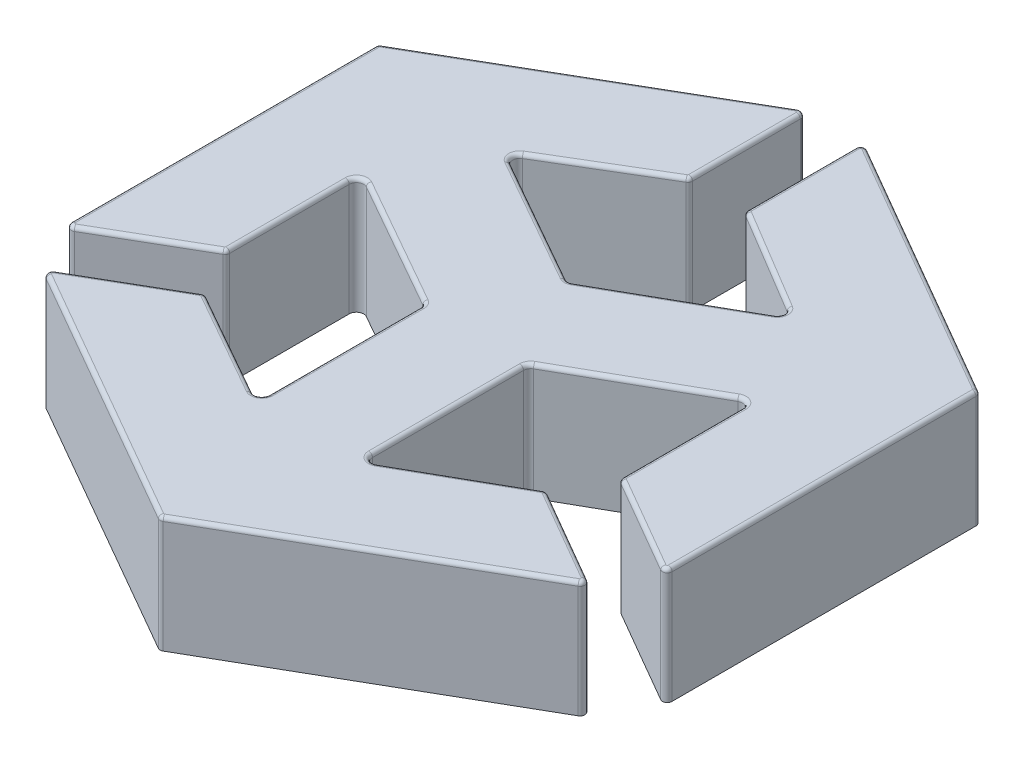
SolidWorks part; units mm, degrees
ref_plane "Front Plane" through (0, 0, 0) normal (0, 0, 1) x (1, 0, 0)
ref_plane "Top Plane" through (0, 0, 0) normal (0, 1, 0) x (1, 0, 0)
ref_plane "Right Plane" through (0, 0, 0) normal (1, 0, 0) x (0, 0, -1)
sketch "Sketch1" plane through (0, 0, 0) normal (0, 1, 0) x (1, 0, 0)
  line L0 (106.3333, 360) -> (531.6667, 360) construction
sketch "Sketch2" plane through (0, 0, 0) normal (0, 1, 0) x (1, 0, 0)
  line L1 (30.6854, 42.3674) -> (17.3949, 49.9061)
  line L2 (17.3796, 51.2019) -> (27.9558, 57.5366)
  line L3 (28.1989, 57.9656) -> (28.1989, 69.1104)
  line L4 (27.4483, 69.5431) -> (0.2494, 53.7902)
  line L5 (0, 53.3576) -> (0, 21.9461)
  line L6 (0.7506, 21.5135) -> (10.4851, 27.1514)
  line L7 (10.7345, 27.5841) -> (10.7345, 39.9383)
  line L8 (11.8546, 40.5907) -> (25.3291, 32.9476)
  line L9 (25.7091, 32.2952) -> (25.7091, 16.6806)
  line L10 (24.589, 16.0282) -> (13.6629, 22.2258)
  line L11 (13.1656, 22.2236) -> (3.5606, 16.6606)
  line L12 (3.5621, 15.7944) -> (30.8064, 0.1431)
  line L13 (33.912, 57.9656) -> (33.912, 69.1104)
  line L14 (44.7313, 51.2019) -> (34.1551, 57.5366)
  line L15 (31.4255, 42.3674) -> (44.716, 49.9061)
  line L16 (50.2563, 40.5907) -> (36.7818, 32.9476)
  line L17 (36.4018, 32.2952) -> (36.4018, 16.6806)
  line L18 (37.5218, 16.0282) -> (48.448, 22.2258)
  line L19 (58.5488, 15.7944) -> (31.3045, 0.1431)
  line L20 (48.9453, 22.2236) -> (58.5503, 16.6606)
  line L21 (61.3603, 21.5135) -> (51.6257, 27.1514)
  line L22 (51.3763, 27.5841) -> (51.3763, 39.9383)
  line L23 (62.1109, 53.3576) -> (62.1109, 21.9461)
  line L24 (34.6626, 69.5431) -> (61.8614, 53.7902)
  arc A0 (31.4255, 42.3674) -> (30.6854, 42.3674) centre (31.0554, 43.0198) cw
  arc A1 (25.3291, 32.9476) -> (25.7091, 32.2952) centre (24.9591, 32.2952) cw
  arc A2 (36.7818, 32.9476) -> (36.4018, 32.2952) centre (37.1518, 32.2952) ccw
  arc A3 (50.2563, 40.5907) -> (51.3763, 39.9383) centre (50.6263, 39.9383) cw
  arc A4 (36.4018, 16.6806) -> (37.5218, 16.0282) centre (37.1518, 16.6806) ccw
  arc A5 (25.7091, 16.6806) -> (24.589, 16.0282) centre (24.9591, 16.6806) cw
  arc A6 (10.7345, 39.9383) -> (11.8546, 40.5907) centre (11.4845, 39.9383) cw
  arc A7 (44.7313, 51.2019) -> (44.716, 49.9061) centre (44.3459, 50.5585) cw
  arc A8 (17.3796, 51.2019) -> (17.3949, 49.9061) centre (17.7649, 50.5585) ccw
  arc A9 (0.2494, 53.7902) -> (0, 53.3576) centre (0.5, 53.3576) ccw
  arc A10 (0, 21.9461) -> (0.7506, 21.5135) centre (0.5, 21.9461) ccw
  arc A11 (10.4851, 27.1514) -> (10.7345, 27.5841) centre (10.2345, 27.5841) ccw
  arc A12 (13.6629, 22.2258) -> (13.1656, 22.2236) centre (13.4162, 21.7909) ccw
  arc A13 (3.5606, 16.6606) -> (3.5621, 15.7944) centre (3.8111, 16.228) ccw
  arc A14 (31.3045, 0.1431) -> (30.8064, 0.1431) centre (31.0554, 0.5766) cw
  arc A15 (58.5488, 15.7944) -> (58.5503, 16.6606) centre (58.2997, 16.228) ccw
  arc A16 (48.448, 22.2258) -> (48.9453, 22.2236) centre (48.6947, 21.7909) cw
  arc A17 (51.6257, 27.1514) -> (51.3763, 27.5841) centre (51.8763, 27.5841) cw
  arc A18 (61.3603, 21.5135) -> (62.1109, 21.9461) centre (61.6109, 21.9461) ccw
  arc A19 (62.1109, 53.3576) -> (61.8614, 53.7902) centre (61.6109, 53.3576) ccw
  arc A20 (33.912, 69.1104) -> (34.6626, 69.5431) centre (34.412, 69.1104) cw
  arc A21 (33.912, 57.9656) -> (34.1551, 57.5366) centre (34.412, 57.9656) ccw
  arc A22 (27.9558, 57.5366) -> (28.1989, 57.9656) centre (27.6989, 57.9656) ccw
  arc A23 (28.1989, 69.1104) -> (27.4483, 69.5431) centre (27.6989, 69.1104) ccw
  point P25 (0, 0)
  dimension "D1" = 0.75
  dimension "D2" = 0.5
extrude "Boss-Extrude1" add sketch "Sketch2" along normal blind 12
fillet "Fillet1" radius 0.4 48 edges at (38.0707, 12, -46.1368) (45.0959, 12, -50.5496) (39.4432, 12, -54.3693) (33.977, 12, -57.7191) (33.912, 12, -63.538) (34.1623, 12, -69.5436) (48.262, 12, -61.6667) (62.044, 12, -53.6073) (62.1109, 12, -37.6519) (61.8606, 12, -21.513) (56.493, 12, -24.3325) (51.4431, 12, -27.3344) (51.3763, 12, -33.7612) (51.0038, 12, -40.5864) (43.519, 12, -36.7691) (36.5037, 12, -32.6727) (36.4018, 12, -24.4879) (36.7743, 12, -16.0325) (42.9849, 12, -19.127) (48.6969, 12, -22.2909) (53.7478, 12, -19.4421) (58.7997, 12, -16.2271) (44.9266, 12, -7.9687) (31.0554, 12, -0.0766) (17.1842, 12, -7.9687) (3.3111, 12, -16.2271) (8.3631, 12, -19.4421) (13.4139, 12, -22.2909) (19.1259, 12, -19.127) (25.3365, 12, -16.0325) (25.7091, 12, -24.4879) (25.6072, 12, -32.6727) (18.5918, 12, -36.7691) (11.1071, 12, -40.5864) (10.7345, 12, -33.7612) (10.6677, 12, -27.3344) (5.6179, 12, -24.3325) (0.2503, 12, -21.513) (0, 12, -37.6519) (0.0668, 12, -53.6073) (13.8488, 12, -61.6667) (27.9486, 12, -69.5436) (28.1989, 12, -63.538) (28.1339, 12, -57.7191) (22.6677, 12, -54.3693) (17.015, 12, -50.5496) (24.0401, 12, -46.1368) (31.0554, 12, -42.2698)
